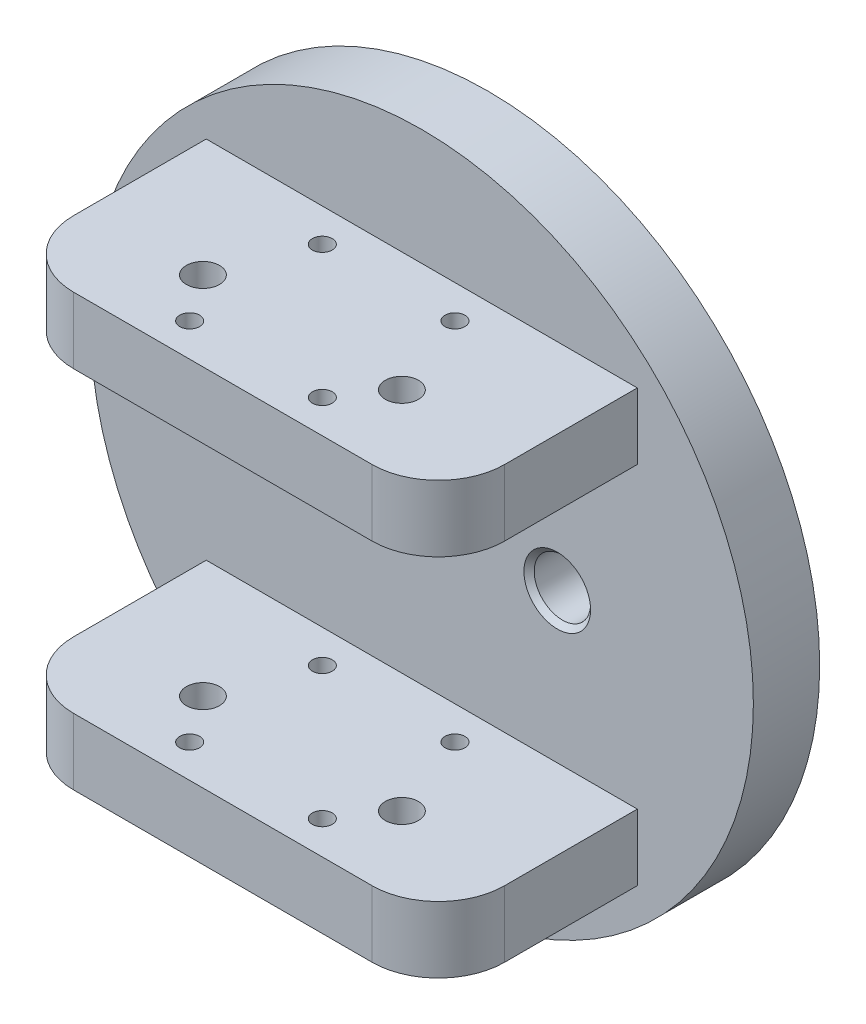
SolidWorks part; units mm, degrees
ref_plane "前视基准面" through (0, 0, 0) normal (0, 0, 1) x (1, 0, 0)
ref_plane "上视基准面" through (0, 0, 0) normal (0, 1, 0) x (1, 0, 0)
ref_plane "右视基准面" through (0, 0, 0) normal (1, 0, 0) x (0, 0, -1)
sketch "草图1" plane through (0, 0, 0) normal (0, 0, 1) x (1, 0, 0)
  circle A0 centre (0, 0) radius 50
  dimension "D1" = 100
extrude "凸台-拉伸1" add sketch "草图1" along normal blind 10
hole_wizard "M10 螺纹孔1" positions "草图7" profile "草图8" tap size "M10" standard "GB" end condition through all
sketch "草图7" plane through (0, 0, 10) normal (0, 0, 1) x (1, 0, 0)
  point P0 (-20.4267, 0)
sketch "草图8" plane through (-20.4267, 0, 10) normal (1, 0, 0) x (0, -1, 0)
  line L0 (0, 0) -> (0, 10)
  line L1 (0, 10) -> (4.25, 10)
  line L2 (4.25, 10) -> (4.25, 0.775)
  line L3 (4.25, 0.775) -> (5.025, 0)
  line L5 (5.025, 0) -> (0, 0)
  line L6 (-4.25, 0.775) -> (-5.025, 0) construction
  line L11 (0, -6.35) -> (0, 107.95) construction
  dimension "通孔螺纹孔钻头直径" = 8.5
  dimension "通孔螺纹孔钻头深度" = 10
  dimension "近端锥形沉头孔直径" = 10.05
  dimension "近端锥形沉头孔角度" = 90
cosmetic thread "孔螺蚊线1" parameters "D2"=10
mirror "镜向2" about plane through (0, 0, 0) normal (1, 0, 0) of "M10 螺纹孔1"
cosmetic thread "孔螺蚊线2" parameters "D2"=10
sketch "草图9" plane through (0, 0, 10) normal (0, 0, 1) x (1, 0, 0)
  line L0 (-32.5, 22.5) -> (32.5, 22.5)
  line L1 (-32.5, 32.5) -> (32.5, 32.5)
  line L2 (-32.5, 32.5) -> (-32.5, 22.5)
  line L3 (-32.5, -32.5) -> (32.5, -32.5)
  line L4 (32.5, 32.5) -> (32.5, 22.5)
  line L5 (-32.5, 32.5) -> (32.5, -32.5) construction
  line L6 (-32.5, -32.5) -> (32.5, 32.5) construction
  line L7 (-32.5, -22.5) -> (32.5, -22.5)
  line L8 (-32.5, -22.5) -> (-32.5, -32.5)
  line L9 (-32.5, 22.5) -> (-32.5, -22.5) construction
  line L10 (32.5, -22.5) -> (32.5, -32.5)
  line L11 (32.5, 22.5) -> (32.5, -22.5) construction
  point P0 (0, 0)
  dimension "D1" = 65
  dimension "D2" = 10
  dimension "D3" = 10
sketch "草图11" plane through (0, 0, 0) normal (0, 1, 0) x (1, 0, 0)
extrude "凸台-拉伸3" add sketch "草图9" along normal blind 30
fillet "圆角2" radius 10 4 edges at (32.5, 27.5, 40) (-32.5, 27.5, 40) (32.5, -27.5, 40) (-32.5, -27.5, 40)
sketch "草图13" plane through (0, 0, 0) normal (0, 1, 0) x (1, 0, 0)
  line L0 (0, 0) -> (0, -43.9412) construction
  line L1 (32.5, -10) -> (-32.5, -10) construction
  line L2 (22.5, -40) -> (-22.5, -40) construction
  circle A0 centre (-10, -15) radius 1.5
  circle A1 centre (-10, -35) radius 1.5
  circle A2 centre (-15, -28) radius 2.5
  circle A3 centre (10, -15) radius 1.5
  circle A5 centre (10, -35) radius 1.5
  circle A6 centre (15, -28) radius 2.5
  point P19 (0, 0)
  point P20 (0, 0)
  point P21 (8.4944, -30.3781)
  point P22 (-17.5409, -40)
  point P23 (-15, -27.5797)
  dimension "D3" = 3
  dimension "D6" = 3
  dimension "D7" = 5
  dimension "D8" = 15
  dimension "D1" = 10
  dimension "D2" = 5
  dimension "D4" = 10
  dimension "D5" = 5
  dimension "D9" = 30
  dimension "D10" = 12
sketch "草图14" plane through (0, 32.5, 0) normal (0, 1, 0) x (1, 0, 0)
  line L0 (0, 0) -> (0, -43.9412) construction
  line L1 (0, 0) -> (0, -43.9412)
  circle A0 centre (-10, -35) radius 1.5 construction
  circle A1 centre (-10, -35) radius 1.5
  circle A2 centre (-15, -28) radius 2.5 construction
  circle A3 centre (-15, -28) radius 2.5
  circle A4 centre (-10, -15) radius 1.5 construction
  circle A5 centre (-10, -15) radius 1.5
  circle A6 centre (10, -15) radius 1.5
  circle A7 centre (15, -28) radius 2.5
  circle A8 centre (10, -35) radius 1.5
extrude "切除-拉伸3" cut sketch "草图14" against normal through all contours A3 | A6 | A7 | A8 | A5 | A1
